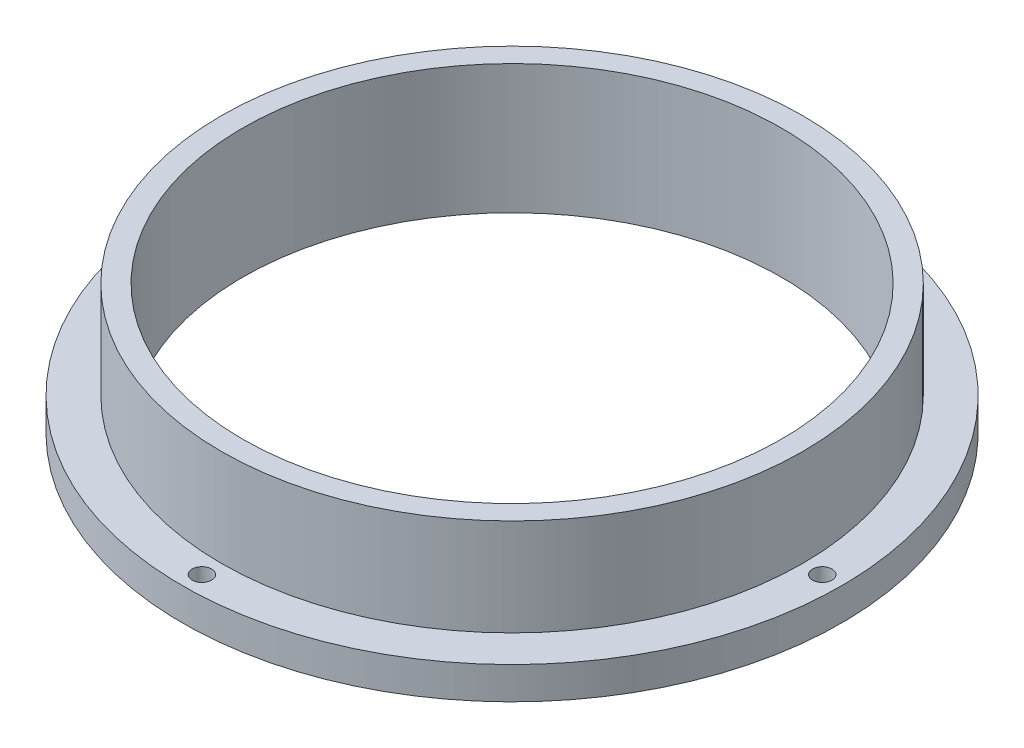
SolidWorks part; units mm, degrees
ref_plane "Front Plane" through (0, 0, 0) normal (0, 0, 1) x (1, 0, 0)
ref_plane "Top Plane" through (0, 0, 0) normal (0, 1, 0) x (1, 0, 0)
ref_plane "Right Plane" through (0, 0, 0) normal (1, 0, 0) x (0, 0, -1)
sketch "Sketch1" plane through (0, 0, 0) normal (0, 1, 0) x (1, 0, 0)
  circle A0 centre (0, 0) radius 42
  circle A1 centre (0, 0) radius 45
  dimension "D1" = 3
extrude "Boss-Extrude1" add sketch "Sketch1" along normal blind 20
sketch "Sketch2" plane through (0, 0, 0) normal (0, -1, 0) x (1, 0, 0)
  line L0 (45, 0) -> (48, 0)
  circle A1 centre (0, 0) radius 42 construction
  circle A2 centre (0, 0) radius 42
  circle A3 centre (0, 0) radius 45 construction
  circle A4 centre (0, 0) radius 45
  circle A5 centre (48, 0) radius 1.5
  circle A6 centre (0, 0) radius 51
  circle A7 centre (0, -48) radius 1.5
  circle A8 centre (-48, 0) radius 1.5
  circle A9 centre (0, 48) radius 1.5
  point P22 (0, 0)
  dimension "D1" = 3
  dimension "D2" = 6
  dimension "D3" = 4
extrude "Boss-Extrude2" add sketch "Sketch2" against normal blind 5
sketch "Sketch3" plane through (0, 20, 0) normal (0, 1, 0) x (1, 0, 0)
  circle A1 centre (0, 0) radius 42 construction
  circle A2 centre (0, 0) radius 41.5
  circle A3 centre (0, 0) radius 41.5
  circle A4 centre (0, 0) radius 42
  dimension "D1" = 0.5
extrude "Boss-Extrude3" add sketch "Sketch3" against normal up to surface (20 mm away) up to face at (0, 0, 42)
sketch "Sketch4" plane through (0, 20, 0) normal (0, 1, 0) x (1, 0, 0)
  circle A0 centre (0, 0) radius 41.5 construction
  circle A1 centre (0, 0) radius 41.5
  circle A2 centre (0, 0) radius 41.7
  dimension "D1" = 0.2
extrude "Cut-Extrude1" cut sketch "Sketch4" against normal through all
